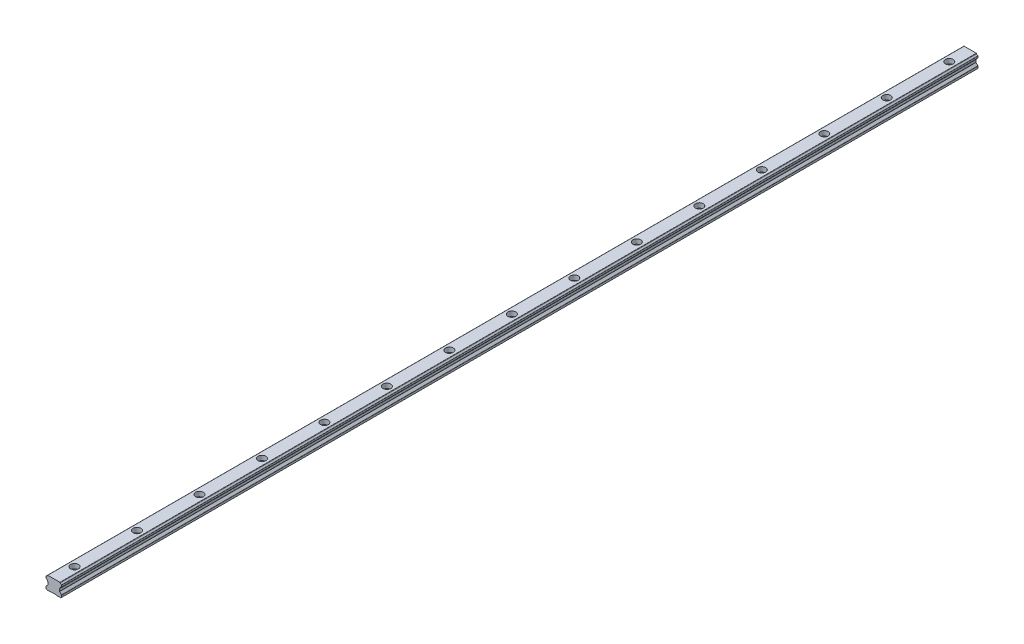
SolidWorks part; units mm, degrees
ref_plane "前视基准面" through (0, 0, 0) normal (0, 0, 1) x (1, 0, 0)
ref_plane "上视基准面" through (0, 0, 0) normal (0, 1, 0) x (1, 0, 0)
ref_plane "右视基准面" through (0, 0, 0) normal (1, 0, 0) x (0, 0, -1)
sketch "草图1" plane through (0, 0, 0) normal (0, 0, 1) x (1, 0, 0)
  line L1 (1192.9337, 427.8946) -> (1188.4838, 427.8946)
  line L2 (1189.4532, 440.3946) -> (1201.1143, 440.3946)
  line L89 (1189.7838, 432.7189) -> (1189.7838, 434.8766)
  line L94 (1189.6959, 435.0887) -> (1189.2646, 435.52)
  line L101 (1187.7838, 428.5946) -> (1187.7838, 430.3877)
  line L103 (1188.4838, 427.8946) -> (1187.7838, 428.5946)
  line L105 (1187.9302, 430.7411) -> (1189.6959, 432.5067)
  line L114 (1187.7838, 437.2641) -> (1187.7838, 438.7253)
  line L139 (1200.8716, 432.5067) -> (1202.6373, 430.7411)
  line L141 (1202.7838, 428.5946) -> (1202.0837, 427.8946)
  line L144 (1197.3338, 428.1946) -> (1193.2337, 428.1946)
  line L149 (1193.2337, 428.1946) -> (1192.9337, 427.8946)
  line L152 (1202.0837, 427.8946) -> (1197.6338, 427.8946)
  line L154 (1197.6338, 427.8946) -> (1197.3338, 428.1946)
  line L155 (1200.7838, 434.8766) -> (1200.7838, 432.7189)
  line L166 (1201.3029, 435.52) -> (1200.8716, 435.0887)
  line L176 (1202.7838, 430.3875) -> (1202.7838, 428.5946)
  line L178 (1202.7838, 438.7252) -> (1202.7838, 437.2639)
  arc A2 (1189.1781, 435.7032) -> (1188.0267, 436.9695) centre (1187.7548, 435.5656) ccw
  arc A3 (1189.6959, 432.5067) -> (1189.7838, 432.7189) centre (1189.4838, 432.7189) ccw
  arc A4 (1189.1781, 435.7032) -> (1189.2646, 435.52) centre (1189.4767, 435.7321) ccw
  arc A5 (1189.7838, 434.8766) -> (1189.6959, 435.0887) centre (1189.4838, 434.8766) ccw
  arc A9 (1187.9302, 430.7411) -> (1187.7838, 430.3877) centre (1188.2838, 430.3875) ccw
  arc A14 (1189.4532, 440.3946) -> (1189.1587, 440.1517) centre (1189.4532, 440.0946) ccw
  arc A17 (1187.7838, 437.2641) -> (1188.0267, 436.9695) centre (1188.0838, 437.2641) ccw
  arc A18 (1188.0267, 439.0197) -> (1187.7838, 438.7253) centre (1188.0838, 438.7252) ccw
  arc A21 (1188.0267, 439.0197) -> (1189.1587, 440.1517) centre (1187.7548, 440.4236) ccw
  arc A22 (1201.4088, 440.1517) -> (1202.5408, 439.0197) centre (1202.8127, 440.4236) ccw
  arc A25 (1202.5408, 436.9695) -> (1201.3894, 435.7032) centre (1202.8127, 435.5656) ccw
  arc A28 (1201.3029, 435.52) -> (1201.3894, 435.7032) centre (1201.0908, 435.7321) ccw
  arc A32 (1200.7838, 432.7189) -> (1200.8716, 432.5067) centre (1201.0838, 432.7189) ccw
  arc A33 (1200.8716, 435.0887) -> (1200.7838, 434.8766) centre (1201.0838, 434.8766) ccw
  arc A34 (1201.4088, 440.1517) -> (1201.1143, 440.3946) centre (1201.1143, 440.0946) ccw
  arc A37 (1202.7838, 430.3875) -> (1202.6373, 430.7411) centre (1202.2838, 430.3875) ccw
  arc A38 (1202.5408, 436.9695) -> (1202.7838, 437.2639) centre (1202.4838, 437.2641) ccw
  arc A41 (1202.7838, 438.7252) -> (1202.5408, 439.0197) centre (1202.4838, 438.7252) ccw
extrude "拉伸1" add sketch "草图1" along normal blind 880
sketch "草图2" plane through (0, 440.3946, 0) normal (0, 1, 0) x (1, 0, 0)
  line L0 (1201.1143, -880) -> (1189.4532, -880) construction
  line L1 (1195.2838, -880) -> (1195.0751, -844.8944) construction
  circle A0 centre (1195.1649, -860) radius 2.25
  dimension "D1" = 4.5
  dimension "D2" = 20
extrude "拉伸2" cut sketch "草图2" against normal up to next
sketch "草图4" plane through (0, 440.3946, 0) normal (0, 1, 0) x (1, 0, 0)
  circle A0 centre (1195.1649, -860) radius 3.75
  dimension "D1" = 7.5
extrude "拉伸10" cut sketch "草图4" against normal blind 4.5
pattern_linear "阵列(线性)1" count 15 spacing 60 along (0, 0, -1) of "拉伸2", "拉伸10"
